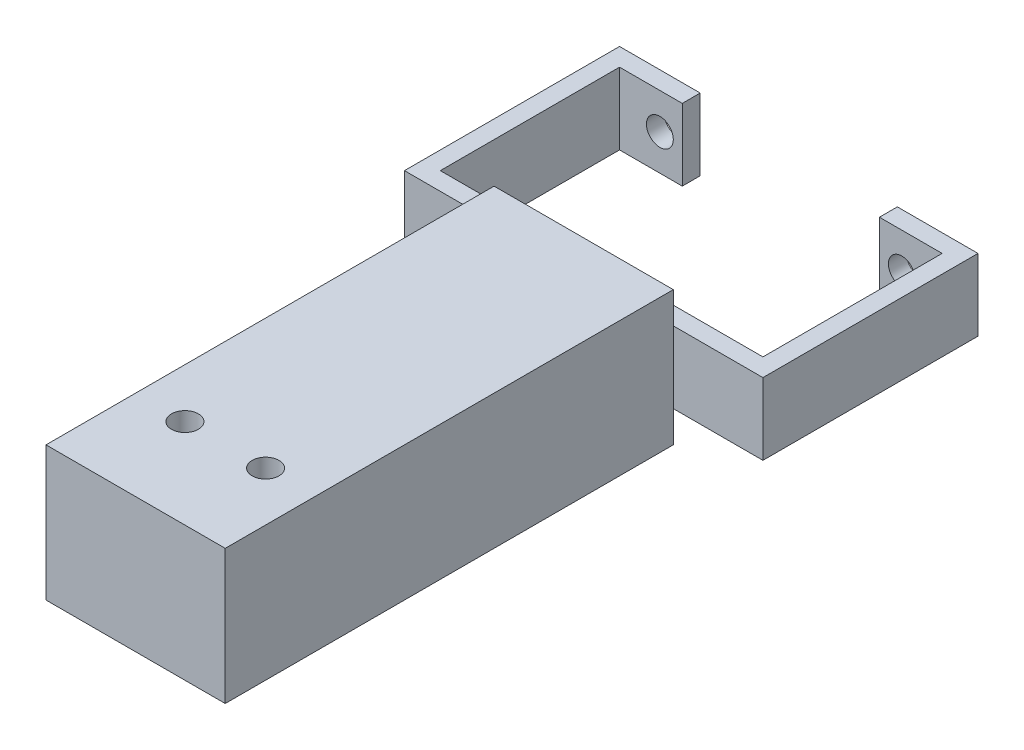
SolidWorks part; units mm, degrees
ref_plane "Спереди" through (0, 0, 0) normal (0, 0, 1) x (1, 0, 0)
ref_plane "Сверху" through (0, 0, 0) normal (0, 1, 0) x (1, 0, 0)
ref_plane "Справа" through (0, 0, 0) normal (1, 0, 0) x (0, 0, -1)
sketch "Эскиз8" plane through (0, 0, 0) normal (0, 0, 1) x (1, 0, 0)
  line L0 (0, 32.4386) -> (0, -46.0572) construction
  line L1 (0, 0) -> (-91.5469, 0) construction
  line L2 (0, 0) -> (73.7671, 0) construction
  line L3 (-20, 4) -> (-20, -4)
  line L5 (-11, 4) -> (-20, 4)
  line L8 (-20, -4) -> (-11, -4)
  line L9 (-11, -4) -> (-11, 4)
  line L10 (0, 0) -> (11, 0) construction
  line L11 (11, -4) -> (11, 4)
  line L12 (11, 4) -> (20, 4)
  line L13 (20, 4) -> (20, -4)
  line L14 (20, -4) -> (11, -4)
  circle A0 centre (-13.5, 0) radius 1.5
  circle A1 centre (13.5, 0) radius 1.5
  point P7 (-11, 0)
  point P11 (-20, 0)
  point P15 (11, 0)
  point P19 (20, 0)
  dimension "D1" = 11
  dimension "D4" = 3
  dimension "D6" = 13.5
  dimension "D2" = 9
  dimension "D3" = 8
  dimension "D5" = 13.5
  dimension "D7" = 11
extrude "Бобышка-Вытянуть1" add sketch "Эскиз8" along normal blind 2
sketch "Эскиз9" plane through (0, 0, 2) normal (0, 0, 1) x (1, 0, 0)
  line L0 (-20, 4) -> (-18, 4)
  line L1 (-11, 4) -> (-20, 4) construction
  line L2 (-18, 4) -> (-18, -4)
  line L3 (-20, -4) -> (-11, -4) construction
  line L4 (-18, -4) -> (-20, -4)
  line L5 (-20, 4) -> (-20, -4) construction
  line L6 (-20, -4) -> (-20, 4)
  line L7 (20, -4) -> (18, -4)
  line L8 (11, -4) -> (20, -4) construction
  line L9 (18, -4) -> (18, 4)
  line L10 (20, 4) -> (11, 4) construction
  line L11 (18, 4) -> (20, 4)
  line L12 (20, 4) -> (20, -4)
  line L13 (-18, 0) -> (0, 0) construction
  line L14 (0, 0) -> (18, 0) construction
  dimension "D1" = 18
extrude "Бобышка-Вытянуть2" add sketch "Эскиз9" along normal blind 20
sketch "Эскиз10" plane through (0, 0, 22) normal (0, 0, 1) x (1, 0, 0)
  line L0 (0, 0) -> (-20, 0) construction
  line L1 (-20, 4) -> (-20, -4) construction
  line L2 (0, 0) -> (20, 0) construction
  line L3 (20, -4) -> (20, 4) construction
  line L4 (-20, -4) -> (-20, 4)
  line L5 (-20, 4) -> (20, 4)
  line L6 (20, 4) -> (20, -4)
  line L7 (20, -4) -> (-20, -4)
extrude "Бобышка-Вытянуть3" add sketch "Эскиз10" along normal blind 2
sketch "Эскиз11" plane through (0, 0, 24) normal (0, 0, 1) x (1, 0, 0)
  line L0 (0, 0) -> (-10, 0) construction
  line L1 (0, 0) -> (10, 0) construction
  line L5 (-10, 7.5) -> (-10, -7.5)
  line L6 (-10, 7.5) -> (10, 7.5)
  line L7 (10, 7.5) -> (10, -7.5)
  line L8 (10, -7.5) -> (-10, -7.5)
  dimension "D1" = 15
  dimension "D2" = 10
extrude "Бобышка-Вытянуть4" add sketch "Эскиз11" along normal blind 50
sketch "Эскиз12" plane through (0, 7.5, 0) normal (0, 1, 0) x (1, 0, 0)
  line L0 (0, -74) -> (0, -24) construction
  line L1 (10, -74) -> (-10, -74) construction
  line L2 (10, -24) -> (-10, -24) construction
  line L3 (-4.5, -64) -> (0, -64) construction
  line L4 (0, -64) -> (4.5, -64) construction
  circle A0 centre (-4.5, -64) radius 1.5
  circle A1 centre (4.5, -64) radius 1.5
  dimension "D1" = 3
  dimension "D2" = 4.5
  dimension "D3" = 10
extrude "Вырез-Вытянуть1" cut sketch "Эскиз12" against normal through all
